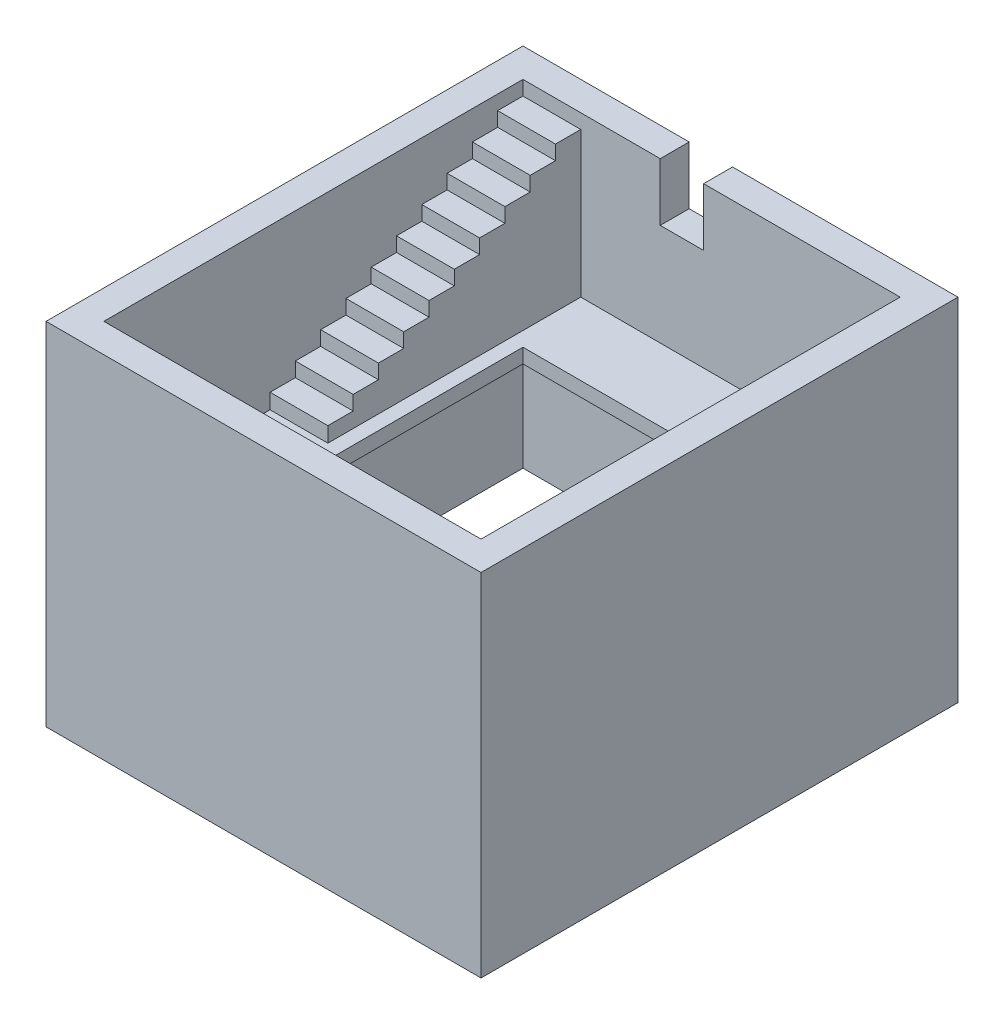
SolidWorks part; units mm, degrees
ref_plane "Alzado" through (0, 0, 0) normal (0, 0, 1) x (1, 0, 0)
ref_plane "Planta" through (0, 0, 0) normal (0, 1, 0) x (1, 0, 0)
ref_plane "Vista lateral" through (0, 0, 0) normal (1, 0, 0) x (0, 0, -1)
sketch "Croquis1" plane through (0, 0, 0) normal (0, 1, 0) x (1, 0, 0)
  line L1 (-3010, -3300) -> (3010, -3300)
  line L2 (-3010, -3300) -> (-3010, 3300)
  line L3 (-3010, 3300) -> (3010, 3300)
  line L4 (3010, -3300) -> (3010, 3300)
  line L5 (-3010, -3300) -> (3010, 3300) construction
  line L6 (-3010, 3300) -> (3010, -3300) construction
  line L7 (-2810, -3100) -> (2810, -3100)
  line L8 (-2810, -3100) -> (-2810, 3100)
  line L9 (-2810, 3100) -> (2810, 3100)
  line L10 (2810, -3100) -> (2810, 3100)
  line L11 (-2810, -3100) -> (2810, 3100) construction
  line L12 (-2810, 3100) -> (2810, -3100) construction
  point P0 (0, 0)
  point P6 (0, 0)
  dimension "D1" = 6020
  dimension "D2" = 6600
  dimension "D3" = 200
  dimension "D4" = 200
extrude "Saliente-Extruir1" add sketch "Croquis1" along normal blind 4860
sketch "Croquis2" plane through (0, 0, 0) normal (0, -1, 0) x (1, 0, 0)
  line L1 (-3010, -3300) -> (3010, -3300)
  line L2 (-3010, -3300) -> (-3010, 3300)
  line L3 (-3010, 3300) -> (3010, 3300)
  line L4 (3010, -3300) -> (3010, 3300)
  line L5 (-3010, -3300) -> (3010, 3300) construction
  line L6 (-3010, 3300) -> (3010, -3300) construction
  point P0 (0, 0)
extrude "Saliente-Extruir2" add sketch "Croquis2" against normal blind 300
sketch "Croquis4" plane through (0, 4860, 0) normal (0, 1, 0) x (1, 0, 0)
  line L1 (2810, -3100) -> (-2810, -3100)
  line L2 (2810, -3100) -> (2810, 3100)
  line L3 (2810, 3100) -> (-2810, 3100)
  line L4 (-2810, -3100) -> (-2810, 3100)
  line L5 (2810, -3100) -> (-2810, 3100) construction
  line L6 (2810, 3100) -> (-2810, -3100) construction
  line L7 (2610, -2900) -> (-2610, -2900)
  line L8 (2610, -2900) -> (2610, 2900)
  line L9 (2610, 2900) -> (-2610, 2900)
  line L10 (-2610, -2900) -> (-2610, 2900)
  line L11 (2610, -2900) -> (-2610, 2900) construction
  line L12 (2610, 2900) -> (-2610, -2900) construction
  point P0 (0, 0)
  point P7 (0, 0)
  dimension "D1" = 200
  dimension "D2" = 200
extrude "Saliente-Extruir3" add sketch "Croquis4" against normal blind 2210
sketch "Croquis5" plane through (0, 0, 0) normal (0, -1, 0) x (1, 0, 0)
  line L0 (3010, -3300) -> (-3010, -3300) construction
  line L1 (-2810, 3100) -> (2810, 3100)
  line L2 (-2810, 3100) -> (-2810, -3100)
  line L3 (-2810, -3100) -> (2810, -3100)
  line L4 (2810, 3100) -> (2810, -3100)
  line L5 (-2810, 3100) -> (2810, -3100) construction
  line L6 (-2810, -3100) -> (2810, 3100) construction
  line L7 (-3010, -3300) -> (-3010, 3300) construction
  point P0 (0, 0)
  dimension "D1" = 200
  dimension "D2" = 200
extrude "Cortar-Extruir1" cut sketch "Croquis5" against normal blind 300
sketch "Croquis7" plane through (0, 2650, 0) normal (0, -1, 0) x (1, 0, 0)
  line L0 (2610, 2900) -> (2610, -2900) construction
  line L1 (-1610, 1900) -> (1610, 1900)
  line L2 (-1610, 1900) -> (-1610, -1900)
  line L3 (-1610, -1900) -> (1610, -1900)
  line L4 (1610, 1900) -> (1610, -1900)
  line L5 (-1610, 1900) -> (1610, -1900) construction
  line L6 (-1610, -1900) -> (1610, 1900) construction
  line L7 (2610, -2900) -> (-2610, -2900) construction
  line L9 (-2810, -3100) -> (2810, -3100)
  line L10 (-2810, -3100) -> (-2810, 3100)
  line L11 (-2810, 3100) -> (2810, 3100)
  line L12 (2810, -3100) -> (2810, 3100)
  line L13 (-2810, -3100) -> (2810, 3100) construction
  line L14 (-2810, 3100) -> (2810, -3100) construction
  point P0 (0, 0)
  point P10 (0, 0)
  dimension "D1" = 1000
  dimension "D2" = 1000
extrude "Saliente-Extruir5" add sketch "Croquis7" along normal blind 200
sketch "Croquis8" plane through (-2610, 0, 0) normal (1, 0, 0) x (0, 0, -1)
  line L1 (2900, 2650) -> (2900, 4860) construction
  line L2 (2900, 4660) -> (2550, 4660)
  line L3 (2550, 4660) -> (2550, 4460)
  line L4 (2550, 4460) -> (2200, 4460)
  line L5 (2200, 4460) -> (2200, 4260)
  line L6 (2200, 4260) -> (1850, 4260)
  line L7 (1850, 4260) -> (1850, 4060)
  line L8 (1850, 4060) -> (1500, 4060)
  line L9 (1500, 4060) -> (1500, 3860)
  line L10 (1500, 3860) -> (1150, 3860)
  line L11 (1150, 3860) -> (1150, 3660)
  line L12 (1150, 3660) -> (800, 3660)
  line L13 (800, 3660) -> (800, 3460)
  line L14 (800, 3460) -> (450, 3460)
  line L15 (450, 3460) -> (450, 3260)
  line L16 (450, 3260) -> (100, 3260)
  line L17 (100, 3260) -> (100, 3060)
  line L18 (100, 3060) -> (-250, 3060)
  line L19 (-250, 3060) -> (-250, 2860)
  line L20 (-250, 2860) -> (-600, 2860)
  line L21 (-600, 2860) -> (-600, 2649.9279)
  line L22 (-600, 2649.9279) -> (2900, 2650)
  line L24 (2900, 2650) -> (2900, 4660)
  dimension "D2" = 350
  dimension "D3" = 200
  dimension "D4" = 350
  dimension "D5" = 200
  dimension "D6" = 350
  dimension "D7" = 200
  dimension "D8" = 350
  dimension "D9" = 200
  dimension "D10" = 350
  dimension "D11" = 200
  dimension "D12" = 350
  dimension "D13" = 200
  dimension "D14" = 350
  dimension "D15" = 200
  dimension "D16" = 350
  dimension "D17" = 200
  dimension "D18" = 350
  dimension "D19" = 200
  dimension "D20" = 350
extrude "Saliente-Extruir6" add sketch "Croquis8" along normal blind 800
sketch "Croquis9" plane through (0, 0, -3300) normal (0, 0, -1) x (-1, 0, 0)
  line L0 (710, 4860) -> (710, 4060)
  line L1 (-3010, 4860) -> (3010, 4860) construction
  line L2 (710, 4060) -> (110, 4060)
  line L3 (110, 4060) -> (110, 4860)
  line L4 (110, 4860) -> (710, 4860)
  line L5 (3010, 4860) -> (3010, 0) construction
  dimension "D1" = 2300
  dimension "D2" = 600
  dimension "D3" = 800
extrude "Cortar-Extruir2" cut sketch "Croquis9" against normal blind 400
